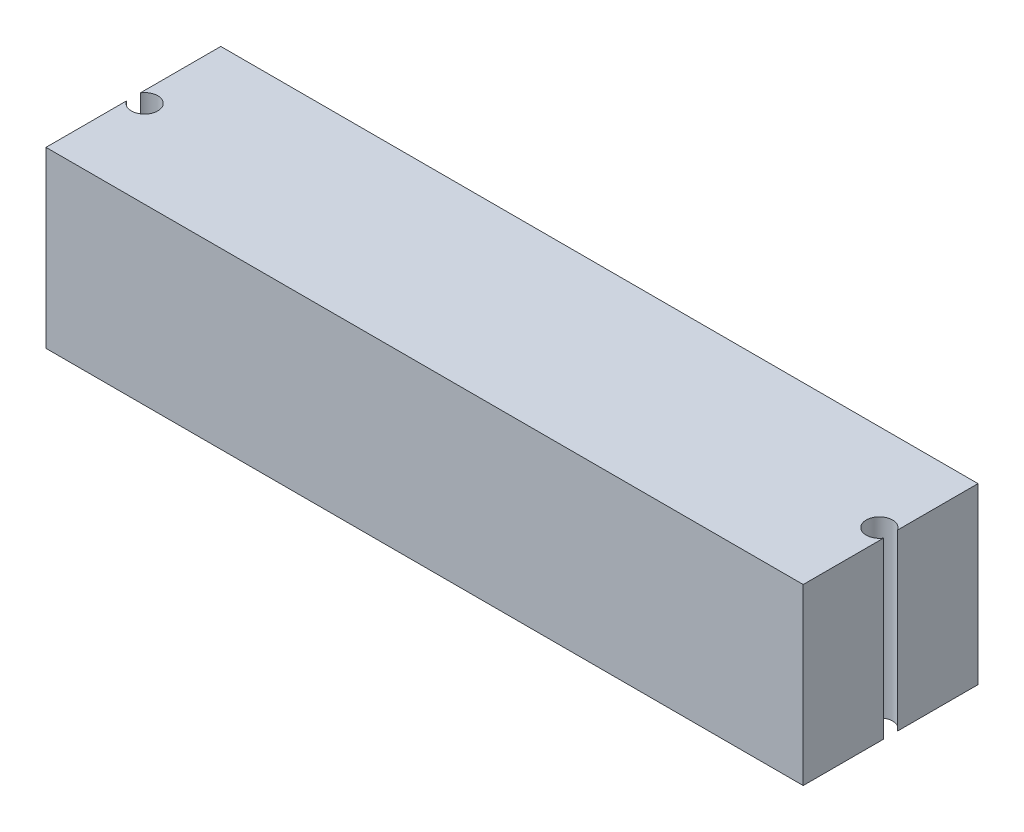
SolidWorks part; units mm, degrees
material "瓦楞纸板盒"
ref_plane "前视基准面" through (0, 0, 0) normal (0, 0, 1) x (1, 0, 0)
ref_plane "上视基准面" through (0, 0, 0) normal (0, 1, 0) x (1, 0, 0)
ref_plane "右视基准面" through (0, 0, 0) normal (1, 0, 0) x (0, 0, -1)
other "Configuration Table"
sketch "草图1" plane through (0, 0, 0) normal (0, 1, 0) x (1, 0, 0)
  line L1 (-15.2433, 11.2946) -> (100.5567, 11.2946)
  line L2 (-15.2433, 11.2946) -> (-15.2433, -15.2054)
  line L3 (-15.2433, -15.2054) -> (100.5567, -15.2054)
  line L4 (100.5567, 11.2946) -> (100.5567, -15.2054)
  dimension "D1" = 26.5
  dimension "D2" = 115.8
extrude "凸台-拉伸1" add sketch "草图1" along normal blind 26.4
sketch "草图2" plane through (0, 26.4, 0) normal (0, 1, 0) x (1, 0, 0)
  line L1 (-15.2433, 11.2946) -> (-15.2433, -15.2054) construction
  line L2 (100.5567, -15.2054) -> (100.5567, 11.2946) construction
  circle A0 centre (-13.0433, -1.9554) radius 2
  circle A1 centre (98.3567, -1.9554) radius 2
  dimension "D1" = 4
  dimension "D2" = 4
  dimension "D3" = 2.2
  dimension "D4" = 2.2
extrude "切除-拉伸5" cut sketch "草图2" against normal through all
sketch "草图3" plane through (100.5567, 0, 0) normal (1, 0, 0) x (0, 0, -1)
  line L0 (-15.2054, 26.4) -> (11.2946, 26.4)
  line L1 (11.2946, 26.4) -> (11.2946, 0)
  line L2 (11.2946, 0) -> (-15.2054, 0)
  line L3 (-15.2054, 0) -> (-15.2054, 26.4)
extrude "切除-拉伸6" cut sketch "草图3" against normal blind 0.5
sketch "草图4" plane through (-15.2433, 0, 0) normal (-1, 0, 0) x (0, 0, 1)
  line L0 (-11.2946, 26.4) -> (15.2054, 26.4)
  line L1 (15.2054, 26.4) -> (15.2054, 0)
  line L2 (15.2054, 0) -> (-11.2946, 0)
  line L3 (-11.2946, 0) -> (-11.2946, 26.4)
extrude "切除-拉伸7" cut sketch "草图4" against normal blind 0.5
